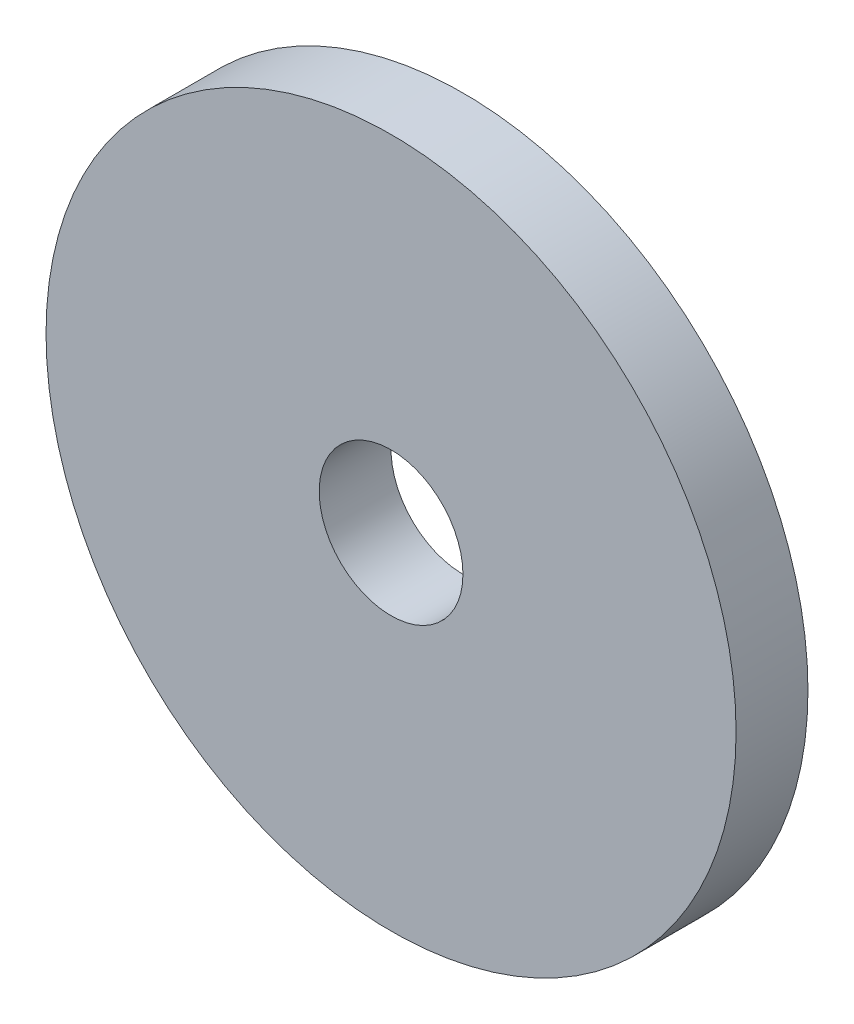
SolidWorks part; units mm, degrees
ref_plane "前视基准面" through (0, 0, 0) normal (0, 0, 1) x (1, 0, 0)
ref_plane "上视基准面" through (0, 0, 0) normal (0, 1, 0) x (1, 0, 0)
ref_plane "右视基准面" through (0, 0, 0) normal (1, 0, 0) x (0, 0, -1)
sketch "草图3" plane through (0, 0, 0) normal (0, 0, 1) x (1, 0, 0)
  circle A0 centre (0, 0) radius 48
extrude "凸台-拉伸2" add sketch "草图3" along normal blind 10
sketch "草图4" plane through (0, 0, 10) normal (0, 0, 1) x (1, 0, 0)
  circle A0 centre (0, 0) radius 10
extrude "切除-拉伸2" cut sketch "草图4" against normal blind 10
